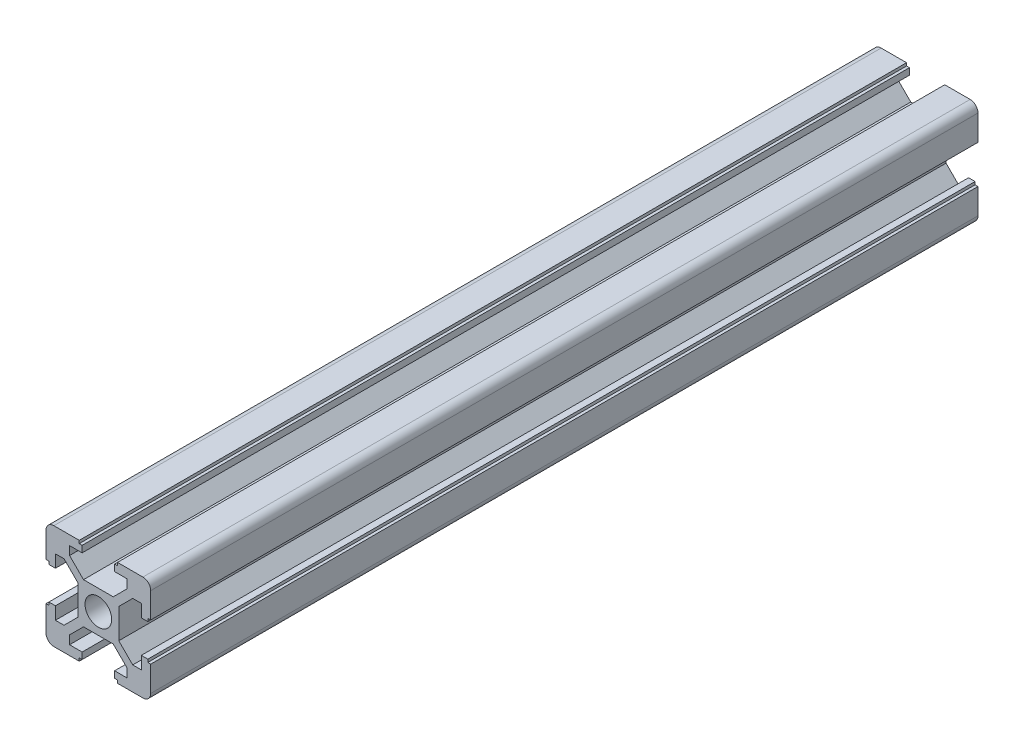
SolidWorks part; units mm, degrees
material "6063-T5"
ref_plane "前视基准面" through (0, 0, 0) normal (0, 0, 1) x (1, 0, 0)
ref_plane "上视基准面" through (0, 0, 0) normal (0, 1, 0) x (1, 0, 0)
ref_plane "右视基准面" through (0, 0, 0) normal (1, 0, 0) x (0, 0, -1)
sketch "草图2" plane through (0, 0, 0) normal (0, 0, 1) x (1, 0, 0)
  line L0 (-3.9, 2.8393) -> (-6.5607, 5.5)
  line L1 (-2.8393, 3.9) -> (2.8393, 3.9)
  line L2 (-3.9, 2.8393) -> (-3.9, -2.8393)
  line L3 (-2.8393, -3.9) -> (2.8393, -3.9)
  line L4 (3.9, 2.8393) -> (3.9, -2.8393)
  line L5 (-3.9, 3.9) -> (3.9, -3.9) construction
  line L6 (-3.9, -3.9) -> (3.9, 3.9) construction
  line L7 (-2.8393, 3.9) -> (-5.5, 6.5607)
  line L8 (-5.5, 6.5607) -> (-5.5, 8.2)
  line L9 (-5.5, 8.2) -> (-3.1, 8.2)
  line L10 (-3.1, 8.2) -> (-3.1, 9.45)
  line L11 (-3.1, 9.45) -> (-3.65, 9.45)
  line L12 (-3.65, 9.45) -> (-3.65, 10)
  line L13 (-3.65, 10) -> (-8.5, 10)
  line L14 (-6.5607, 5.5) -> (-8.2, 5.5)
  line L15 (-10, 3.65) -> (-10, 8.5)
  line L16 (-9.45, 3.65) -> (-10, 3.65)
  line L17 (-9.45, 3.1) -> (-9.45, 3.65)
  line L18 (-8.2, 3.1) -> (-9.45, 3.1)
  line L19 (-8.2, 5.5) -> (-8.2, 3.1)
  line L20 (2.8393, 3.9) -> (5.5, 6.5607)
  line L21 (3.9, 2.8393) -> (6.5607, 5.5)
  line L22 (6.5607, 5.5) -> (8.2, 5.5)
  line L23 (8.2, 5.5) -> (8.2, 3.1)
  line L24 (8.2, 3.1) -> (9.45, 3.1)
  line L25 (9.45, 3.1) -> (9.45, 3.65)
  line L26 (9.45, 3.65) -> (10, 3.65)
  line L27 (10, 3.65) -> (10, 8.5)
  line L28 (5.5, 6.5607) -> (5.5, 8.2)
  line L29 (3.65, 10) -> (8.5, 10)
  line L30 (3.65, 9.45) -> (3.65, 10)
  line L31 (3.1, 9.45) -> (3.65, 9.45)
  line L32 (3.1, 8.2) -> (3.1, 9.45)
  line L33 (5.5, 8.2) -> (3.1, 8.2)
  line L34 (3.9, -2.8393) -> (6.5607, -5.5)
  line L35 (2.8393, -3.9) -> (5.5, -6.5607)
  line L36 (5.5, -6.5607) -> (5.5, -8.2)
  line L37 (5.5, -8.2) -> (3.1, -8.2)
  line L38 (3.1, -8.2) -> (3.1, -9.45)
  line L39 (3.1, -9.45) -> (3.65, -9.45)
  line L40 (3.65, -9.45) -> (3.65, -10)
  line L41 (3.65, -10) -> (8.5, -10)
  line L42 (6.5607, -5.5) -> (8.2, -5.5)
  line L43 (10, -3.65) -> (10, -8.5)
  line L44 (9.45, -3.65) -> (10, -3.65)
  line L45 (9.45, -3.1) -> (9.45, -3.65)
  line L46 (8.2, -3.1) -> (9.45, -3.1)
  line L47 (8.2, -5.5) -> (8.2, -3.1)
  line L48 (-2.8393, -3.9) -> (-5.5, -6.5607)
  line L49 (-3.9, -2.8393) -> (-6.5607, -5.5)
  line L50 (-6.5607, -5.5) -> (-8.2, -5.5)
  line L51 (-8.2, -5.5) -> (-8.2, -3.1)
  line L52 (-8.2, -3.1) -> (-9.45, -3.1)
  line L53 (-9.45, -3.1) -> (-9.45, -3.65)
  line L54 (-9.45, -3.65) -> (-10, -3.65)
  line L55 (-10, -3.65) -> (-10, -8.5)
  line L56 (-5.5, -6.5607) -> (-5.5, -8.2)
  line L57 (-3.65, -10) -> (-8.5, -10)
  line L58 (-3.65, -9.45) -> (-3.65, -10)
  line L59 (-3.1, -9.45) -> (-3.65, -9.45)
  line L60 (-3.1, -8.2) -> (-3.1, -9.45)
  line L61 (-5.5, -8.2) -> (-3.1, -8.2)
  circle A0 centre (0, 0) radius 2.55
  arc A1 (-8.5, 10) -> (-10, 8.5) centre (-8.5, 8.5) ccw
  arc A2 (10, 8.5) -> (8.5, 10) centre (8.5, 8.5) ccw
  arc A3 (8.5, -10) -> (10, -8.5) centre (8.5, -8.5) ccw
  arc A4 (-10, -8.5) -> (-8.5, -10) centre (-8.5, -8.5) ccw
  point P25 (-10, 10)
  point P79 (0, 0)
  dimension "D1" = 5.1
  dimension "D9" = 1.5
  dimension "D2" = 7.8
  dimension "D3" = 1.5
  dimension "D4" = 10
  dimension "D5" = 3.1
  dimension "D6" = 0.55
  dimension "D7" = 1.8
  dimension "D8" = 5.5
  dimension "D11" = 3.9
  dimension "D10" = 4
extrude "凸台-拉伸1" add sketch "草图2" along normal blind 158
